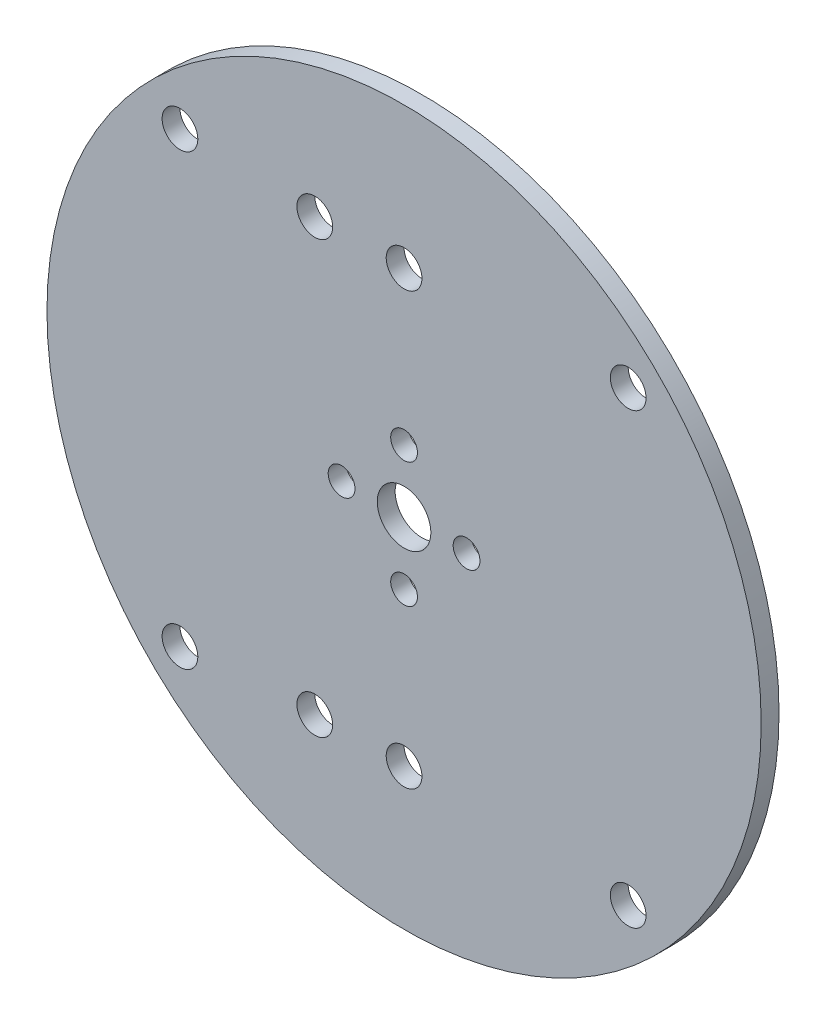
SolidWorks part; units mm, degrees
material "普通碳钢"
ref_plane "前视" through (0, 0, 0) normal (0, 0, 1) x (1, 0, 0)
ref_plane "上视" through (0, 0, 0) normal (0, 1, 0) x (1, 0, 0)
ref_plane "右视" through (0, 0, 0) normal (1, 0, 0) x (0, 0, -1)
sketch "草图1" plane through (0, 0, 0) normal (0, 0, 1) x (1, 0, 0)
  circle A0 centre (89.8449, 65.6716) radius 2
  circle A1 centre (39.6403, 15.467) radius 2
  circle A2 centre (39.6403, 65.6716) radius 2
  circle A3 centre (54.7426, 64.7143) radius 2
  circle A4 centre (64.7426, 64.7143) radius 2
  circle A5 centre (89.8449, 15.467) radius 2
  circle A6 centre (64.7426, 16.4143) radius 2
  circle A7 centre (57.7426, 40.5693) radius 1.5
  circle A8 centre (64.7426, 33.5693) radius 1.5
  circle A9 centre (71.7426, 40.5693) radius 1.5
  circle A10 centre (64.7426, 47.5693) radius 1.5
  circle A11 centre (64.7426, 40.5693) radius 3
  circle A12 centre (64.7426, 40.5693) radius 40
  circle A13 centre (54.7426, 16.4143) radius 2
  dimension "D1" = 4
extrude "凸台-拉伸1" add sketch "草图1" along normal blind 2
